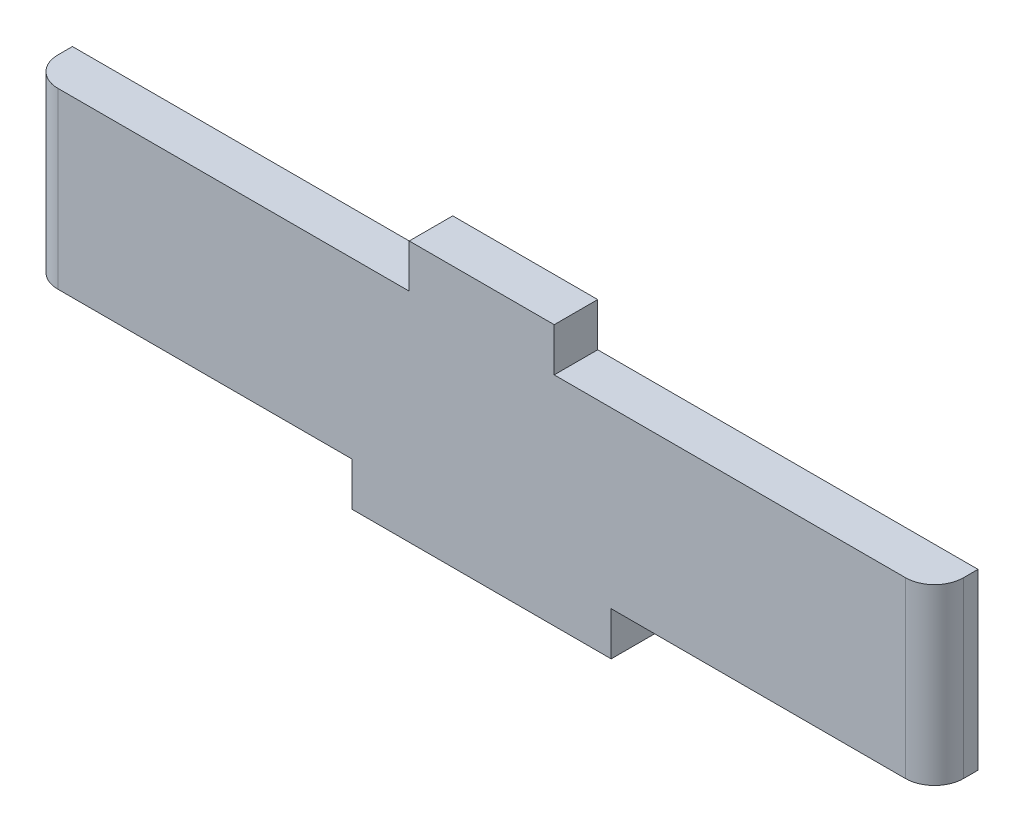
SolidWorks part; units mm, degrees
ref_plane "Front Plane" through (0, 0, 0) normal (0, 0, 1) x (1, 0, 0)
ref_plane "Top Plane" through (0, 0, 0) normal (0, 1, 0) x (1, 0, 0)
ref_plane "Right Plane" through (0, 0, 0) normal (1, 0, 0) x (0, 0, -1)
sketch "Sketch1" plane through (0, 0, 0) normal (0, 0, 1) x (1, 0, 0)
  line L1 (-31.23, 9) -> (31.23, 9)
  line L2 (-31.23, 9) -> (-31.23, -9)
  line L3 (-31.23, -9) -> (31.23, -9)
  line L4 (31.23, 9) -> (31.23, -9)
  line L5 (-31.23, 9) -> (31.23, -9) construction
  line L6 (-31.23, -9) -> (31.23, 9) construction
  point P0 (0, 0)
  dimension "D1" = 18
  dimension "D2" = 62.46
extrude "Boss-Extrude1" add sketch "Sketch1" along normal blind 3
sketch "Sketch2" plane through (0, 0, 3) normal (0, 0, 1) x (1, 0, 0)
  line L1 (31.23, -9) -> (8.93, -9)
  line L2 (31.23, -9) -> (31.23, -6)
  line L3 (31.23, -6) -> (8.93, -6)
  line L4 (8.93, -9) -> (8.93, -6)
  line L5 (-31.23, -9) -> (-8.94, -9)
  line L6 (-31.23, -9) -> (-31.23, -6)
  line L7 (-31.23, -6) -> (-8.94, -6)
  line L8 (-8.94, -9) -> (-8.94, -6)
  line L9 (31.23, 9) -> (5, 9)
  line L10 (31.23, 9) -> (31.23, 6)
  line L11 (31.23, 6) -> (5, 6)
  line L12 (5, 9) -> (5, 6)
  line L13 (-31.23, 9) -> (-5, 9)
  line L14 (-31.23, 9) -> (-31.23, 6)
  line L15 (-31.23, 6) -> (-5, 6)
  line L16 (-5, 9) -> (-5, 6)
  dimension "D1" = 3
  dimension "D2" = 3
  dimension "D3" = 17.87
  dimension "D4" = 22.3
  dimension "D5" = 3
  dimension "D6" = 3
  dimension "D7" = 10
  dimension "D8" = 26.23
extrude "Cut-Extrude1" cut sketch "Sketch2" against normal blind 3
fillet "Fillet1" radius 2 1 edges at (31.23, 0, 3)
fillet "Fillet2" radius 2 1 edges at (-31.23, 0, 3)
